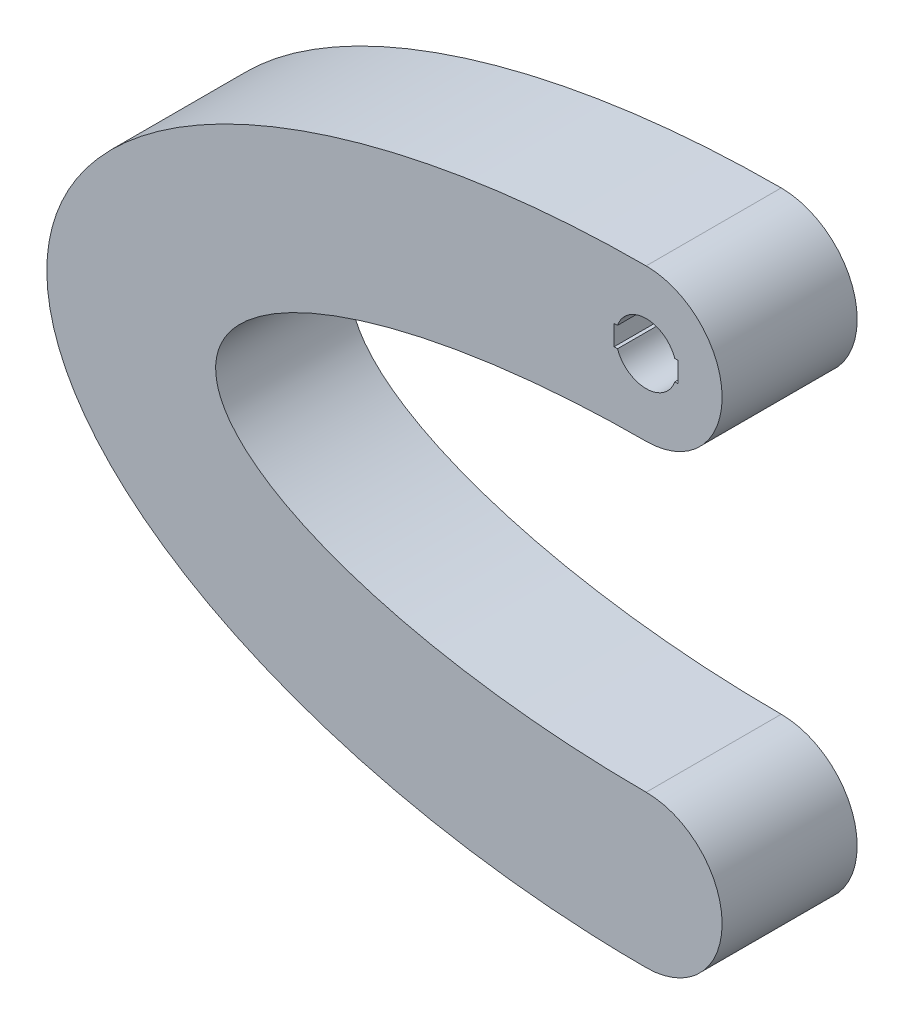
SolidWorks part; units mm, degrees
ref_plane "Front Plane" through (0, 0, 0) normal (0, 0, 1) x (1, 0, 0)
ref_plane "Top Plane" through (0, 0, 0) normal (0, 1, 0) x (1, 0, 0)
ref_plane "Right Plane" through (0, 0, 0) normal (1, 0, 0) x (0, 0, -1)
sketch "Sketch1" plane through (0, 0, 0) normal (0, 0, 1) x (1, 0, 0)
  line L0 (0, 0) -> (19.375, 0) construction
  line L5 (19.375, 0) -> (19.375, 22.5) construction
  line L6 (0, 0) -> (-25, 0) construction
  arc A0 (19.375, 22.5) -> (19.375, 11.25) centre (19.375, 16.875) cw
  arc A1 (19.375, -22.5) -> (19.375, -11.25) centre (19.375, -16.875) ccw
  ellipse E0 centre (19.375, 0) end of major axis (-25, 0) minor radius 22.5 (19.375, -22.5) -> (19.375, 22.5) cw
  ellipse E1 centre (19.375, 0) end of major axis (-12.5, 0) minor radius 11.25 (19.375, -11.25) -> (19.375, 11.25) cw
  point P17 (-12.5, 0)
  dimension "D3" = 5.625
  dimension "D1" = 19.375
  dimension "D2" = 22.5
  dimension "D4" = 25
  dimension "D5" = 12.5
extrude "Boss-Extrude1" add sketch "Sketch1" along normal blind 10
sketch "Sketch3" plane through (0, 0, 10) normal (0, 0, 1) x (1, 0, 0)
  line L0 (19.375, 22.5) -> (19.375, 11.25)
  line L2 (17.25, 16.125) -> (21.5, 16.125)
  line L3 (17.25, 16.125) -> (17.25, 17.625)
  line L4 (17.25, 17.625) -> (21.5, 17.625)
  line L5 (21.5, 16.125) -> (21.5, 17.625)
  line L6 (17.25, 16.125) -> (21.5, 17.625) construction
  line L7 (17.25, 17.625) -> (21.5, 16.125) construction
  arc A0 (19.375, 11.25) -> (19.375, 22.5) centre (19.375, 16.875) ccw construction
  circle A1 centre (19.375, 16.875) radius 2
  dimension "D1" = 4
  dimension "D2" = 4.25
  dimension "D3" = 1.5
extrude "Cut-Extrude2" cut sketch "Sketch3" against normal blind 8 contours L4 A1 L0 | L0 A1 L4 | L2 A1 L0 | L0 A1 L2
sketch "Sketch4" plane through (0, 0, 10) normal (0, 0, 1) x (1, 0, 0)
  line L0 (17.2537, 17.625) -> (17, 17.625)
  line L1 (17.2537, 16.125) -> (17, 16.125)
  line L2 (17, 16.125) -> (17, 17.625)
  line L3 (17.25, 17.6145) -> (17.25, 17.625)
  line L4 (21.4963, 16.125) -> (21.75, 16.125)
  line L5 (21.75, 16.125) -> (21.75, 17.625)
  line L6 (21.75, 17.625) -> (21.4963, 17.625)
  line L7 (17.25, 16.125) -> (17.25, 17.625) construction
  line L8 (17.25, 17.625) -> (17.521, 17.625) construction
  line L9 (21.229, 17.625) -> (21.5, 17.625) construction
  line L10 (21.5, 16.125) -> (21.5, 17.625) construction
  line L11 (21.5, 17.6145) -> (21.5, 17.625)
  line L13 (21.229, 16.125) -> (21.5, 16.125) construction
  line L14 (17.25, 16.125) -> (17.521, 16.125) construction
  line L15 (21.4963, 17.625) -> (21.5, 17.625)
  line L16 (21.5, 16.125) -> (21.5, 16.1355)
  line L17 (21.4963, 16.125) -> (21.5, 16.125)
  line L18 (17.25, 16.125) -> (17.2537, 16.125)
  line L19 (17.25, 16.125) -> (17.25, 16.1355)
  line L20 (17.25, 17.625) -> (17.2537, 17.625)
  arc A0 (21.5, 17.6145) -> (17.25, 17.6145) centre (19.375, 16.875) ccw
  arc A7 (17.25, 16.1355) -> (21.5, 16.1355) centre (19.375, 16.875) ccw
  line M10 (17.25, 17.625) -> (17.521, 17.625)
  arc M11 (17.521, 17.625) -> (21.229, 17.625) centre (19.375, 16.875) cw
  line M12 (21.229, 17.625) -> (21.5, 17.625)
  line M13 (21.5, 17.625) -> (21.5, 16.125)
  line M14 (21.5, 16.125) -> (21.229, 16.125)
  arc M15 (21.229, 16.125) -> (17.521, 16.125) centre (19.375, 16.875) cw
  line M16 (17.521, 16.125) -> (17.25, 16.125)
  line M17 (17.25, 16.125) -> (17.25, 17.625)
  dimension "D1" = 4.5
  dimension "D4" = 0.25
  dimension "D2" = 0.25
  dimension "D3" = 0.25
extrude "Cut-Extrude3" cut sketch "Sketch4" against normal through all contours A7 A0 M17 M16 M15 M14 M13 M12 M11 M10 | L2 L1 L0 M17 | L5 L6 L4 M13 | A7 M16 M14 M15 | A0 M12 M10 M11
